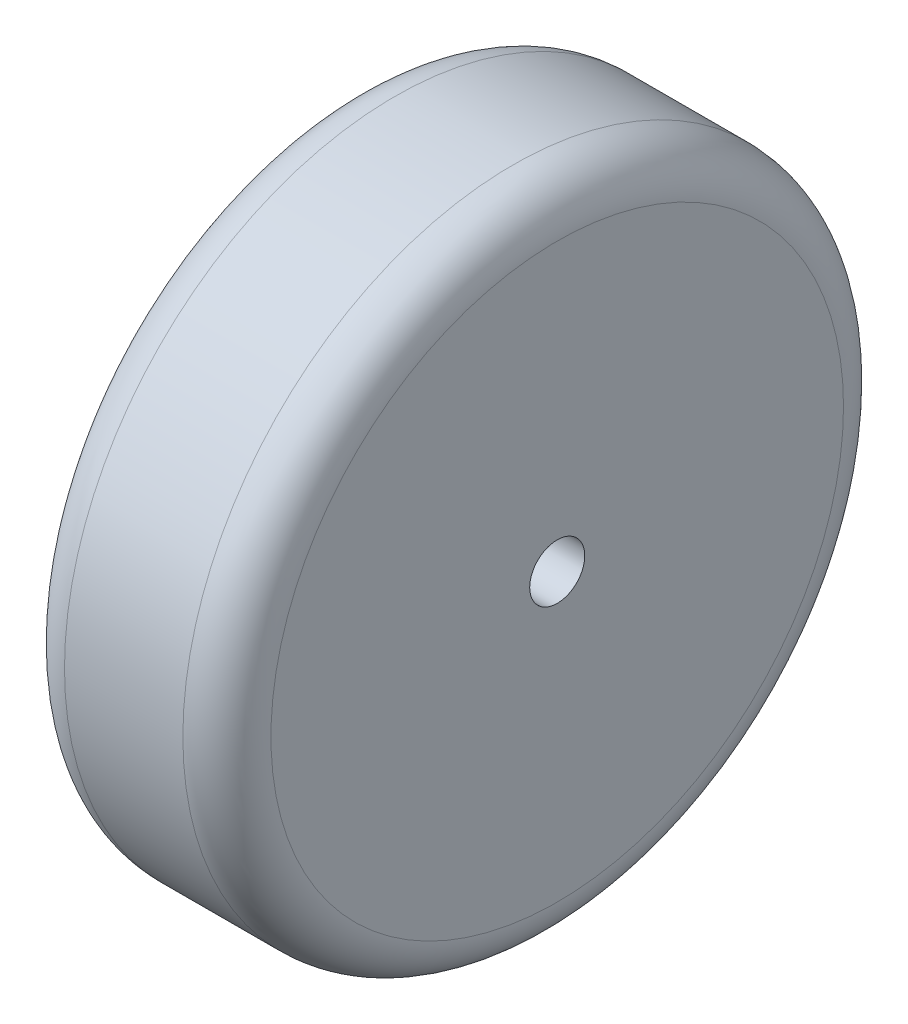
SolidWorks part; units mm, degrees
ref_plane "Front Plane" through (0, 0, 0) normal (0, 0, 1) x (1, 0, 0)
ref_plane "Top Plane" through (0, 0, 0) normal (0, 1, 0) x (1, 0, 0)
ref_plane "Right Plane" through (0, 0, 0) normal (1, 0, 0) x (0, 0, -1)
sketch "Sketch1" plane through (0, 0, 0) normal (0, 1, 0) x (1, 0, 0)
  line L0 (11.9062, -38.1) -> (-11.9062, -38.1)
  line L1 (-11.9062, -38.1) -> (-11.9062, -3.175)
  line L2 (-11.9062, -3.175) -> (11.9062, -3.175)
  line L3 (11.9062, -3.175) -> (11.9062, -38.1)
  line L4 (-11.9062, 0) -> (11.9062, 0) construction
  point P7 (0, 0)
  point P8 (0, 0)
  point P9 (0, 0)
  dimension "D1" = 23.8125
  dimension "D2" = 76.2
  dimension "D3" = 6.35
revolve "Revolve1" add sketch "Sketch1" angle 360 about L4
fillet "Fillet1" radius 5.08 2 edges at (-11.9062, 0, 38.1) (11.9062, 0, 38.1)
